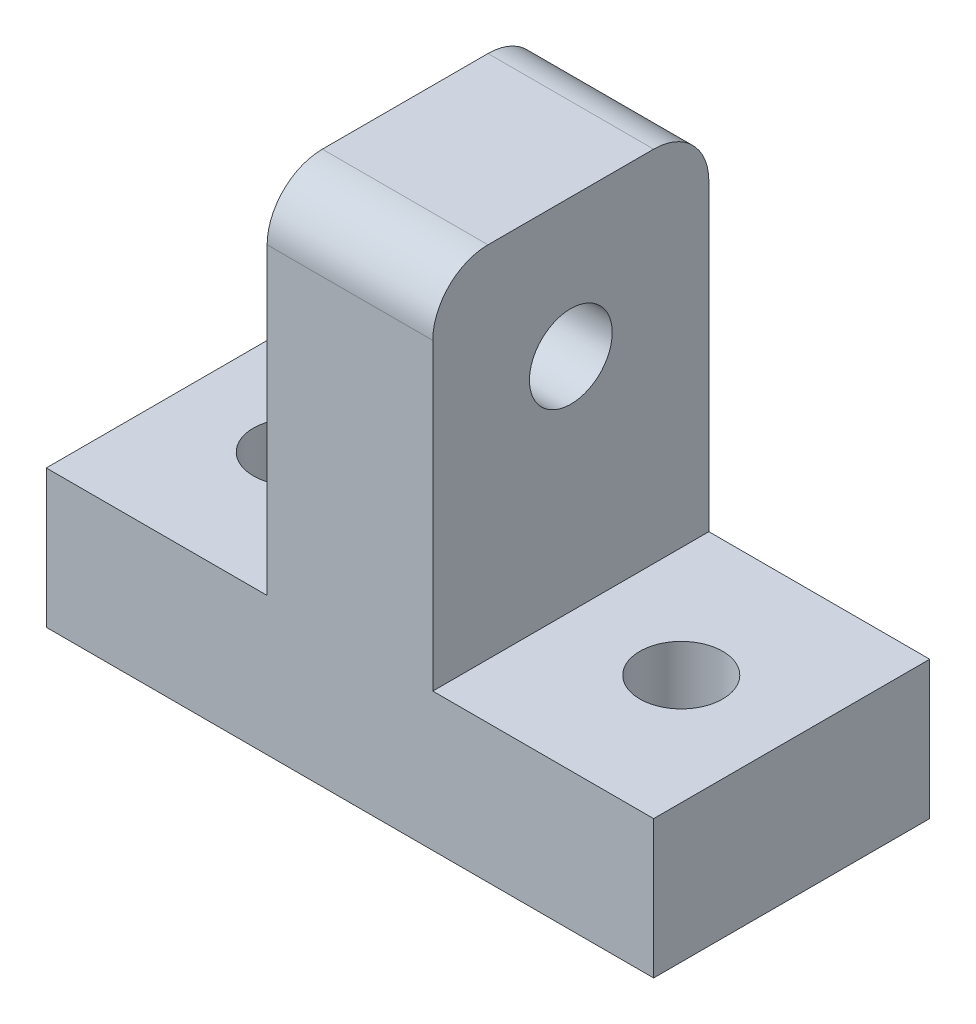
SolidWorks part; units mm, degrees
ref_plane "Front" through (0, 0, 0) normal (0, 0, 1) x (1, 0, 0)
ref_plane "Top" through (0, 0, 0) normal (0, 1, 0) x (1, 0, 0)
ref_plane "Right" through (0, 0, 0) normal (1, 0, 0) x (0, 0, -1)
sketch "Sketch1" plane through (0, 0, 0) normal (0, 1, 0) x (1, 0, 0)
  line L1 (-11, -5) -> (11, -5)
  line L2 (-11, -5) -> (-11, 5)
  line L3 (-11, 5) -> (11, 5)
  line L4 (11, -5) -> (11, 5)
  line L5 (-11, -5) -> (11, 5) construction
  line L6 (-11, 5) -> (11, -5) construction
  circle A2 centre (-7, 0) radius 1.5
  circle A3 centre (7, 0) radius 1.5
  point P0 (0, 0)
  dimension "D3" = 3
  dimension "D4" = 3
  dimension "D5" = 4
  dimension "D6" = 4
  dimension "D1" = 10
  dimension "D2" = 22
extrude "Boss-Extrude1" add sketch "Sketch1" along normal blind 5
sketch "Sketch4" plane through (0, 5, 0) normal (0, 1, 0) x (1, 0, 0)
  line L0 (11, 5) -> (-11, 5) construction
  line L1 (-3, -5) -> (3, -5)
  line L2 (-3, -5) -> (-3, 5)
  line L3 (-3, 5) -> (3, 5)
  line L4 (3, -5) -> (3, 5)
  line L5 (-3, -5) -> (3, 5) construction
  line L6 (-3, 5) -> (3, -5) construction
  circle A0 centre (-7, 0) radius 1.5 construction
  point P0 (0, 0)
  dimension "D1" = 4
extrude "Boss-Extrude3" add sketch "Sketch4" along normal blind 13
sketch "Sketch5" plane through (3, 0, 0) normal (1, 0, 0) x (0, 0, -1)
  line L0 (0, 18) -> (0, 5) construction
  line L1 (5, 18) -> (-5, 18) construction
  line L2 (5, 5) -> (-5, 5) construction
  circle A0 centre (0, 13) radius 1.5
  point P10 (0, 12.8943)
  dimension "D1" = 3
  dimension "D2" = 8
extrude "Cut-Extrude1" cut sketch "Sketch5" against normal up to next
fillet "Fillet1" radius 2 2 edges at (0, 18, -5) (0, 18, 5)
